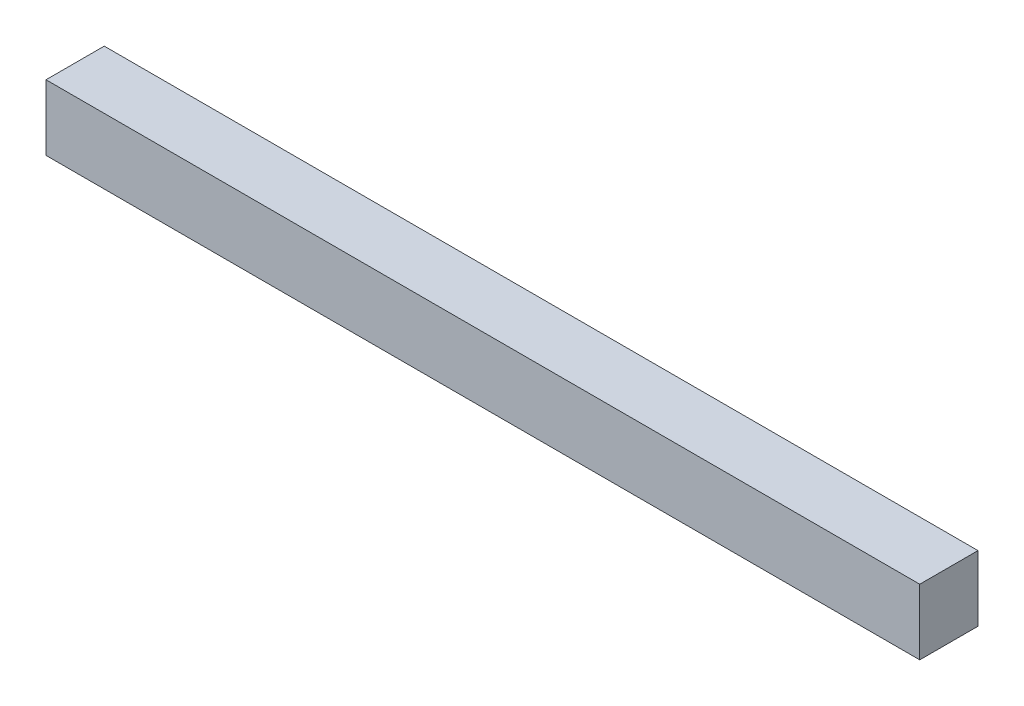
SolidWorks part; units mm, degrees
ref_plane "Plan de face" through (0, 0, 0) normal (0, 0, 1) x (1, 0, 0)
ref_plane "Plan de dessus" through (0, 0, 0) normal (0, 1, 0) x (1, 0, 0)
ref_plane "Plan de droite" through (0, 0, 0) normal (1, 0, 0) x (0, 0, -1)
sketch "Esquisse1" plane through (0, 0, 0) normal (0, 0, 1) x (1, 0, 0)
  line L1 (-33.3401, 11.1359) -> (86.6599, 11.1359)
  line L2 (-33.3401, 11.1359) -> (-33.3401, 2.1359)
  line L3 (-33.3401, 2.1359) -> (86.6599, 2.1359)
  line L4 (86.6599, 11.1359) -> (86.6599, 2.1359)
  dimension "D1" = 120
  dimension "D2" = 9
extrude "Extrusion1" add sketch "Esquisse1" along normal blind 8
